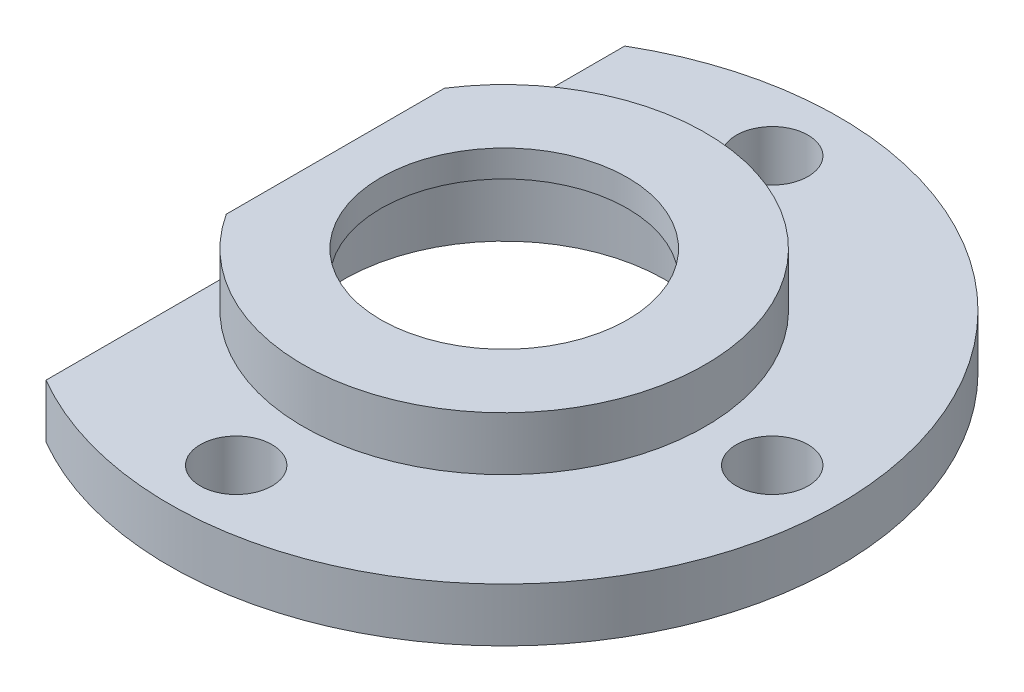
SolidWorks part; units mm, degrees
ref_plane "Front Plane" through (0, 0, 0) normal (0, 0, 1) x (1, 0, 0)
ref_plane "Top Plane" through (0, 0, 0) normal (0, 1, 0) x (1, 0, 0)
ref_plane "Right Plane" through (0, 0, 0) normal (1, 0, 0) x (0, 0, -1)
sketch "Sketch1" plane through (0, 0, 0) normal (0, 1, 0) x (1, 0, 0)
  circle A0 centre (0, 0) radius 15.875
  dimension "D1" = 31.75
extrude "Boss-Extrude1" add sketch "Sketch1" along normal blind 2.54
sketch "Sketch2" plane through (0, 2.54, 0) normal (0, 1, 0) x (1, 0, 0)
  circle A0 centre (0, 0) radius 9.525
  dimension "D1" = 19.05
extrude "Boss-Extrude2" add sketch "Sketch2" along normal blind 2.54
sketch "Sketch3" plane through (0, 0, 0) normal (0, -1, 0) x (1, 0, 0)
  circle A0 centre (0, 0) radius 7.62
  dimension "D1" = 15.24
extrude "Cut-Extrude1" cut sketch "Sketch3" against normal blind 3.81
sketch "Sketch4" plane through (0, 5.08, 0) normal (0, 1, 0) x (1, 0, 0)
  circle A0 centre (0, 0) radius 5.842
  dimension "D1" = 11.684
extrude "Cut-Extrude2" cut sketch "Sketch4" against normal up to next
sketch "Sketch5" plane through (0, 2.54, 0) normal (0, 1, 0) x (1, 0, 0)
  line L0 (0, 15.875) -> (0, 0) construction
  circle A0 centre (0, 12.7) radius 1.7
  circle A1 centre (0, 0) radius 15.875 construction
  circle A2 centre (12.7, 0) radius 1.7
  circle A3 centre (0, -12.7) radius 1.7
  circle A4 centre (-12.7, 0) radius 1.7
  point P18 (0, 0)
  dimension "D2" = 3.4
  dimension "D1" = 12.7
  dimension "D3" = 4
extrude "Cut-Extrude3" cut sketch "Sketch5" against normal up to next
sketch "Sketch6" plane through (0, 2.54, 0) normal (0, 1, 0) x (1, 0, 0)
  line L0 (-8, -13.7119) -> (-8, 13.7119)
  circle A1 centre (0, 0) radius 15.875 construction
  arc A2 (-8, -13.7119) -> (-8, 13.7119) centre (0, 0) cw
  circle M4 centre (-12.7, 0) radius 1.7
  circle M5 centre (0, 0) radius 9.525
  circle M6 centre (0, 0) radius 15.875
  dimension "D1" = 8
extrude "Cut-Extrude5" cut sketch "Sketch6" against normal up to next and the other way blind 2.794 contours L0 M5 | L0 M6 M5 M4
